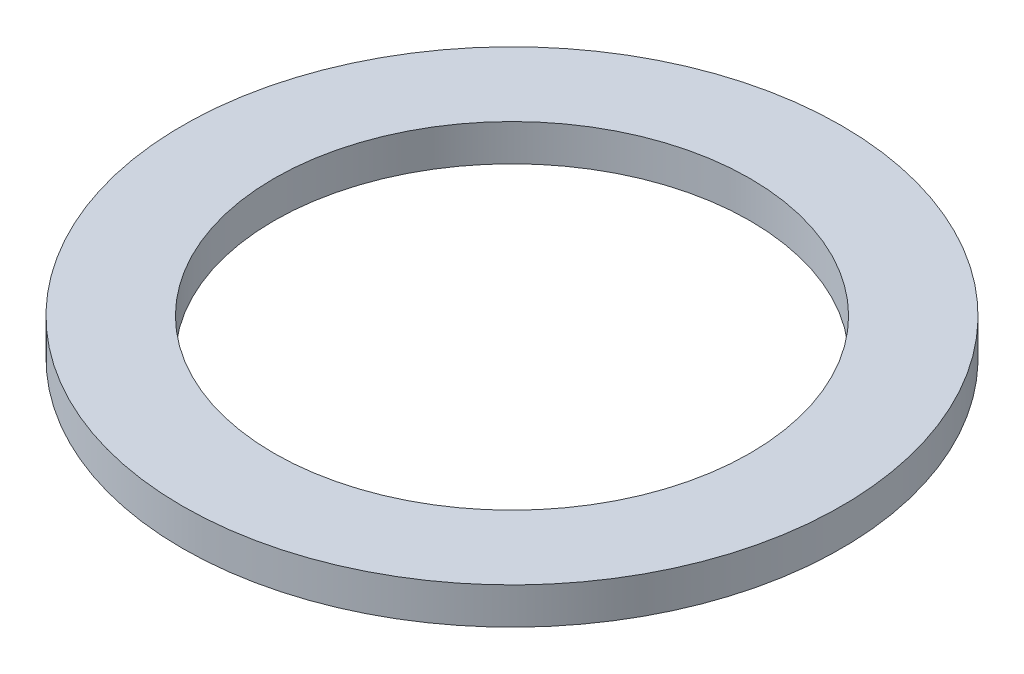
SolidWorks part; units mm, degrees
ref_plane "前视基准面" through (0, 0, 0) normal (0, 0, 1) x (1, 0, 0)
ref_plane "上视基准面" through (0, 0, 0) normal (0, 1, 0) x (1, 0, 0)
ref_plane "右视基准面" through (0, 0, 0) normal (1, 0, 0) x (0, 0, -1)
sketch "草图1" plane through (0, 0, 0) normal (0, 1, 0) x (1, 0, 0)
  circle A0 centre (0, 0) radius 32.5
  circle A1 centre (0, 0) radius 45
  dimension "D1" = 65
  dimension "D2" = 90
extrude "凸台-拉伸1" add sketch "草图1" along normal blind 5 contours A1 A0
